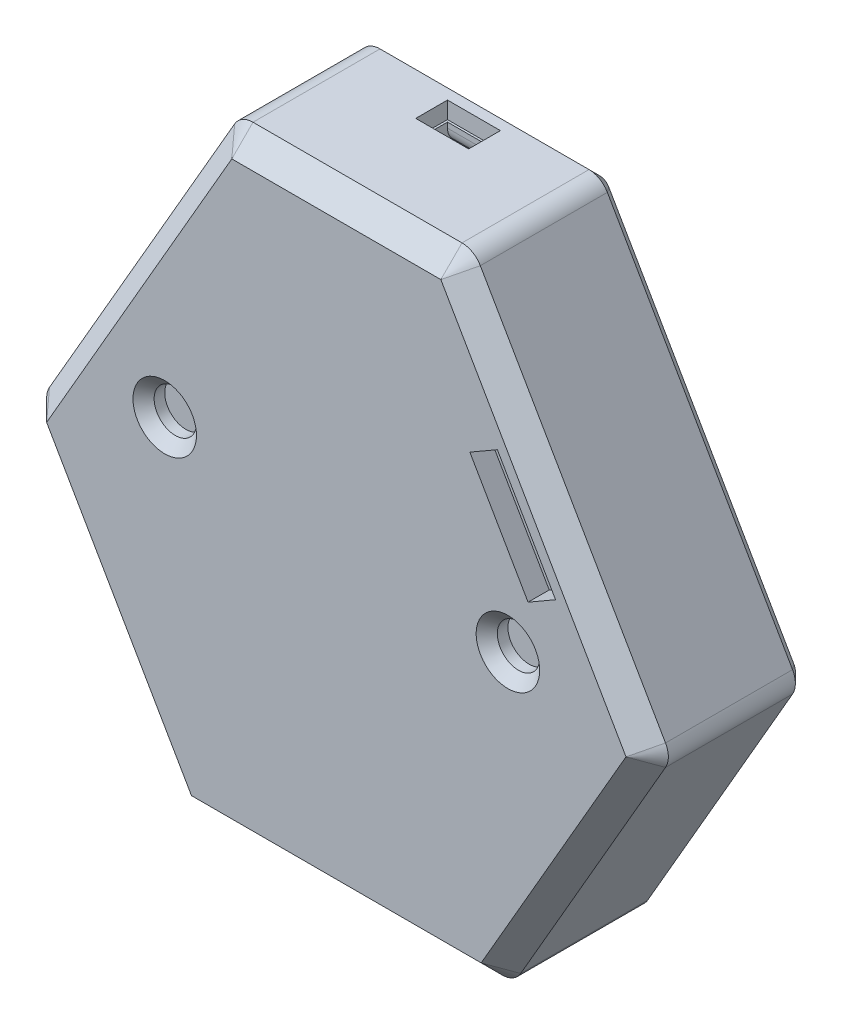
SolidWorks part; units mm, degrees
ref_plane "Front Plane" through (0, 0, 0) normal (0, 0, 1) x (1, 0, 0)
ref_plane "Top Plane" through (0, 0, 0) normal (0, 1, 0) x (1, 0, 0)
ref_plane "Right Plane" through (0, 0, 0) normal (1, 0, 0) x (0, 0, -1)
sketch "Sketch1" plane through (0, 0, 0) normal (0, 0, 1) x (1, 0, 0)
  line L0 (0, 0) -> (26.2117, 0) construction
  line L1 (13.1059, -22.7) -> (26.2117, 0)
  line L2 (26.2117, 0) -> (13.1059, 22.7)
  line L3 (13.1059, 22.7) -> (-13.1059, 22.7) construction
  line L4 (-13.1059, 22.7) -> (-26.2117, 0)
  line L5 (-26.2117, 0) -> (-13.1059, -22.7)
  line L6 (-13.1059, -22.7) -> (13.1059, -22.7)
  line L7 (-13.1059, 22.7) -> (-9.2953, 29.3)
  line L8 (-9.2953, 29.3) -> (9.2953, 29.3)
  line L9 (9.2953, 29.3) -> (13.1059, 22.7)
  line L10 (0, 29.3) -> (0, 22.7) construction
  line L11 (9.9882, 30.5) -> (14.1451, 23.3)
  line L12 (27.5973, 0) -> (14.1451, 23.3)
  line L13 (13.7987, -23.9) -> (27.5973, 0)
  line L14 (-13.7987, -23.9) -> (13.7987, -23.9)
  line L15 (-27.5973, 0) -> (-13.7987, -23.9)
  line L16 (-14.1451, 23.3) -> (-27.5973, 0)
  line L17 (-14.1451, 23.3) -> (-9.9882, 30.5)
  line L18 (-9.9882, 30.5) -> (9.9882, 30.5)
  circle A0 centre (0, 0) radius 22.7 construction
  dimension "D1" = 45.4
  dimension "D2" = 52.4234
  dimension "D3" = 52
  dimension "D4" = 26.2117
  dimension "D5" = 18.5907
  dimension "D6" = 1.2
extrude "Boss-Extrude1" add sketch "Sketch1" along normal blind 6
sketch "Sketch2" plane through (0, 0, 0) normal (0, 0, -1) x (-1, 0, 0)
  line L0 (-15.5, 18.5532) -> (-15.5, -18.5532)
  line L1 (-26.2117, 0) -> (-9.2953, 29.3) construction
  line L2 (-13.1059, -22.7) -> (-26.2117, 0) construction
  line L3 (-15.5, -18.5532) -> (15.5, -18.5532) construction
  line L4 (26.2117, 0) -> (13.1059, -22.7) construction
  line L5 (15.5, -18.5532) -> (15.5, 18.5532)
  line L6 (9.9882, 30.5) -> (-9.9882, 30.5)
  line L7 (-9.9882, 30.5) -> (-27.5973, 0)
  line L8 (-27.5973, 0) -> (-13.7987, -23.9)
  line L9 (-13.7987, -23.9) -> (13.7987, -23.9)
  line L10 (13.7987, -23.9) -> (27.5973, 0)
  line L11 (27.5973, 0) -> (9.9882, 30.5)
  line L12 (9.9882, 30.5) -> (-9.9882, 30.5)
  line L13 (-9.9882, 30.5) -> (-27.5973, 0)
  line L14 (-27.5973, 0) -> (-13.7987, -23.9)
  line L15 (-13.7987, -23.9) -> (13.7987, -23.9)
  line L16 (13.7987, -23.9) -> (27.5973, 0)
  line L17 (27.5973, 0) -> (9.9882, 30.5)
  line L18 (9.2953, 29.3) -> (26.2117, 0) construction
  line L19 (0, 0) -> (0, -18.5532) construction
  line M10 (9.9882, 30.5) -> (-9.9882, 30.5)
  line M11 (-9.9882, 30.5) -> (-27.5973, 0)
  line M12 (-27.5973, 0) -> (-13.7987, -23.9)
  line M13 (-13.7987, -23.9) -> (13.7987, -23.9)
  line M14 (13.7987, -23.9) -> (27.5973, 0)
  line M15 (27.5973, 0) -> (9.9882, 30.5)
  line M16 (-26.2117, 0) -> (-9.2953, 29.3)
  line M17 (-9.2953, 29.3) -> (9.2953, 29.3)
  line M18 (9.2953, 29.3) -> (26.2117, 0)
  line M19 (26.2117, 0) -> (13.1059, -22.7)
  line M20 (13.1059, -22.7) -> (-13.1059, -22.7)
  line M21 (-13.1059, -22.7) -> (-26.2117, 0)
  dimension "D2" = 31
  dimension "D1" = 0
extrude "Boss-Extrude2" add sketch "Sketch2" along normal blind 7 contours L0 M16 M21 | M15 M10 M11 M12 M13 M14 M21 M16 M17 M18 M19 M20 | L5 M19 M18
sketch "Sketch4" plane through (0, 0, 0) normal (0, 0, 1) x (1, 0, 0)
  line L0 (26.2117, 0) -> (15.5, 0)
  line L1 (15.5, 18.5532) -> (15.5, -18.5532) construction
  line M2 (26.2117, 0) -> (15.5, 18.5532)
  line M3 (15.5, 18.5532) -> (15.5, -18.5532)
extrude "Cut-Extrude1" cut sketch "Sketch4" against normal blind 3 and the other way through all contours L0 M2 M3
sketch "Sketch6" plane through (0, 0, -7) normal (0, 0, -1) x (-1, 0, 0)
  line L0 (-27.5973, 0) -> (-13.7987, -23.9) construction
  line L1 (-13.7987, -23.9) -> (13.7987, -23.9) construction
  line L2 (13.7987, -23.9) -> (27.5973, 0) construction
  line L3 (27.5973, 0) -> (9.9882, 30.5) construction
  line L4 (9.9882, 30.5) -> (-9.9882, 30.5) construction
  line L5 (-9.9882, 30.5) -> (-27.5973, 0) construction
  line L6 (-27.5973, 0) -> (-13.7987, -23.9)
  line L7 (-13.7987, -23.9) -> (13.7987, -23.9)
  line L8 (13.7987, -23.9) -> (27.5973, 0)
  line L9 (27.5973, 0) -> (9.9882, 30.5)
  line L10 (9.9882, 30.5) -> (-9.9882, 30.5)
  line L11 (-9.9882, 30.5) -> (-27.5973, 0)
extrude "Boss-Extrude3" add sketch "Sketch6" along normal blind 2
chamfer "Chamfer2" distance 2 angle 45 6 edges at (0, 30.5, -9) (-18.7928, 15.25, -9) (-20.698, -11.95, -9) (0, -23.9, -9) (20.698, -11.95, -9) (18.7928, 15.25, -9)
sketch "Sketch7" plane through (0, 0, -7) normal (0, 0, 1) x (1, 0, 0)
  line L0 (-10.45, 27.3) -> (10.45, 27.3)
  line L1 (-9.2953, 29.3) -> (-26.2117, 0) construction
  line L2 (15.5, 18.5532) -> (9.2953, 29.3) construction
  line L3 (9.2953, 29.3) -> (-9.2953, 29.3) construction
  line L4 (26.2117, 0) -> (9.2953, 29.3) construction
  line L5 (9.2953, 29.3) -> (-9.2953, 29.3) construction
  line L6 (-9.2953, 29.3) -> (-15.5, 18.5532) construction
  line L7 (10.45, 27.3) -> (9.2953, 29.3)
  line L8 (9.2953, 29.3) -> (-9.2953, 29.3)
  line L9 (-9.2953, 29.3) -> (-10.45, 27.3)
  dimension "D1" = 2
extrude "Boss-Extrude4" add sketch "Sketch7" along normal blind 8.5
sketch "Sketch8" plane through (0, 0, 6) normal (0, 0, 1) x (1, 0, 0)
  line L0 (-27.5973, 0) -> (-13.7987, -23.9) construction
  line L1 (-13.7987, -23.9) -> (13.7987, -23.9) construction
  line L2 (13.7987, -23.9) -> (27.5973, 0) construction
  line L3 (27.5973, 0) -> (9.9882, 30.5) construction
  line L4 (9.9882, 30.5) -> (-9.9882, 30.5) construction
  line L5 (-9.9882, 30.5) -> (-27.5973, 0) construction
  line L6 (-27.5973, 0) -> (-13.7987, -23.9)
  line L7 (-13.7987, -23.9) -> (13.7987, -23.9)
  line L8 (13.7987, -23.9) -> (27.5973, 0)
  line L9 (27.5973, 0) -> (9.9882, 30.5)
  line L10 (9.9882, 30.5) -> (-9.9882, 30.5)
  line L11 (-9.9882, 30.5) -> (-27.5973, 0)
  line L12 (10.1036, 30.7) -> (-10.1036, 30.7)
  line L13 (-10.1036, 30.7) -> (-27.8283, 0)
  line L14 (-27.8283, 0) -> (-13.9141, -24.1)
  line L15 (-13.9141, -24.1) -> (13.9141, -24.1)
  line L16 (13.9141, -24.1) -> (27.8283, 0)
  line L17 (27.8283, 0) -> (10.1036, 30.7)
  line L18 (11.0274, 32.3) -> (-11.0274, 32.3)
  line L19 (-11.0274, 32.3) -> (-29.6758, 0)
  line L20 (-29.6758, 0) -> (-14.8379, -25.7)
  line L21 (-14.8379, -25.7) -> (14.8379, -25.7)
  line L22 (14.8379, -25.7) -> (29.6758, 0)
  line L23 (29.6758, 0) -> (11.0274, 32.3)
  dimension "D1" = 0.2
  dimension "D2" = 1.6
extrude "Boss-Extrude5" add sketch "Sketch8" against normal blind 13 separate body contours L22 L23 L18 L19 L20 L21 L17 L16 L15 L14 L13 L12
sketch "Sketch9" plane through (0, 0, 6) normal (0, 0, 1) x (1, 0, 0)
  line L0 (-29.6758, 0) -> (-14.8379, -25.7) construction
  line L1 (-14.8379, -25.7) -> (14.8379, -25.7) construction
  line L2 (14.8379, -25.7) -> (29.6758, 0) construction
  line L3 (29.6758, 0) -> (11.0274, 32.3) construction
  line L4 (11.0274, 32.3) -> (-11.0274, 32.3) construction
  line L5 (-11.0274, 32.3) -> (-29.6758, 0) construction
  line L6 (-29.6758, 0) -> (-14.8379, -25.7)
  line L7 (-14.8379, -25.7) -> (14.8379, -25.7)
  line L8 (14.8379, -25.7) -> (29.6758, 0)
  line L9 (29.6758, 0) -> (11.0274, 32.3)
  line L10 (11.0274, 32.3) -> (-11.0274, 32.3)
  line L11 (-11.0274, 32.3) -> (-29.6758, 0)
extrude "Boss-Extrude6" add sketch "Sketch9" along normal blind 2
sketch "Sketch10" plane through (0, 0, 6) normal (0, 0, 1) x (1, 0, 0)
  line L0 (20.7117, 9.5263) -> (18.1136, 8.0263)
  line L1 (26.2117, 0) -> (9.2953, 29.3) construction
  line L2 (18.1136, 8.0263) -> (12.6136, 17.5526)
  line L3 (12.6136, 17.5526) -> (15.2117, 19.0526)
  line L4 (15.5, 18.5532) -> (10.45, 27.3) construction
  circle A0 centre (-16.2117, 6) radius 2
  circle A1 centre (16.2117, 3) radius 2
  line M10 (9.2953, 29.3) -> (26.2117, 0)
  dimension "D4" = 4
  dimension "D5" = 4
  dimension "D1" = 3
  dimension "D2" = 11
  dimension "D3" = 11
  dimension "D6" = 10
  dimension "D7" = 3
  dimension "D8" = 10
  dimension "D9" = 6
extrude "Cut-Extrude2" cut sketch "Sketch10" along normal through all contours A0 | A1 | L3 L2 L0 M10
fillet "Fillet2" radius 2 6 edges at (29.6758, 0, 0.5) (11.0274, 32.3, 0.5) (-11.0274, 32.3, 0.5) (-29.6758, 0, 0.5) (-14.8379, -25.7, 0.5) (14.8379, -25.7, 0.5)
chamfer "Chamfer3" distance 2 angle 45 12 edges at (-22.2569, -12.85, 8) (-14.6832, -25.4321, 8) (-29.3664, 0, 8) (0, -25.7, 8) (-20.3516, 16.15, 8) (14.6832, -25.4321, 8) (-10.8727, 32.0321, 8) (22.2569, -12.85, 8) (0, 32.3, 8) (29.3664, 0, 8) (10.8727, 32.0321, 8) (20.3516, 16.15, 8)
chamfer "Chamfer4" distance 1 angle 45 14 edges at (22.2569, -12.85, -7) (29.3664, 0, -7) (14.6832, -25.4321, -7) (20.3516, 16.15, -7) (0, -25.7, -7) (10.8727, 32.0321, -7) (-14.6832, -25.4321, -7) (0, 32.3, -7) (-22.2569, -12.85, -7) (-10.8727, 32.0321, -7) (-29.3664, 0, -7) (-20.3516, 16.15, -7) (-14.2117, 6, 8) (18.2117, 3, 8)
chamfer "Chamfer5" distance 1 angle 45 2 edges at (0, -22.7, -7) (0, 27.3, -7)
sketch "Sketch12" plane through (0, 0, -9) normal (0, 0, -1) x (-1, 0, 0)
  line L0 (8.8335, 28.5) -> (-8.8335, 28.5) construction
  line L1 (-2.5, 28.5) -> (2.5, 28.5)
  line L2 (-2.5, 28.5) -> (-2.5, 25.5)
  line L3 (-2.5, 25.5) -> (2.5, 25.5)
  line L4 (2.5, 28.5) -> (2.5, 25.5)
  point P4 (0, 28.5)
  point P7 (0, 28.5)
  dimension "D1" = 3
  dimension "D2" = 5
extrude "Cut-Extrude3" cut sketch "Sketch12" against normal up to next
sketch "Sketch13" plane through (0, 32.3, 0) normal (0, 1, 0) x (1, 0, 0)
  line L0 (0, 5) -> (0, 6) construction
  line L1 (-2.5, 5) -> (2.5, 5)
  line L2 (-2.5, 5) -> (-2.5, 2)
  line L3 (-2.5, 2) -> (2.5, 2)
  line L4 (2.5, 5) -> (2.5, 2)
  line L5 (9.8727, 6) -> (-9.8727, 6) construction
  dimension "D1" = 3
  dimension "D2" = 5
  dimension "D3" = 1
extrude "Cut-Extrude4" cut sketch "Sketch13" against normal up to surface (3.8 mm away) up to face at (0, 28.5, -3.75)
sketch "Sketch14" plane through (0, 30.5, 0) normal (0, 1, 0) x (1, 0, 0)
  line L0 (-2.5, 2) -> (2.5, 2) construction
  line L1 (2.5, 2) -> (2.5, 5) construction
  line L2 (2.5, 5) -> (-2.5, 5) construction
  line L3 (-2.5, 5) -> (-2.5, 2) construction
  line L4 (-2.5, 2) -> (2.5, 2)
  line L5 (2.5, 2) -> (2.5, 5)
  line L6 (2.5, 5) -> (-2.5, 5)
  line L7 (-2.5, 5) -> (-2.5, 2)
extrude "Cut-Extrude5" cut sketch "Sketch14" against normal up to next (2 mm away)
fillet "Fillet4" radius 1.5 1 edges at (0, 28.5, -5)
